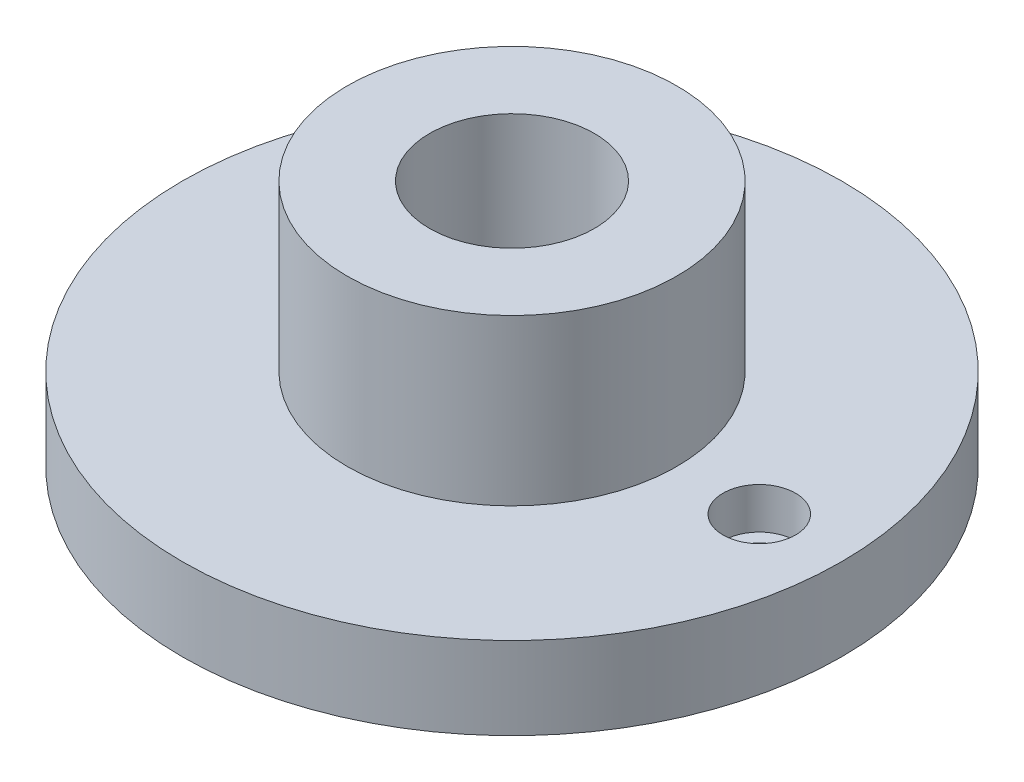
SolidWorks part; units mm, degrees
ref_plane "Front Plane" through (0, 0, 0) normal (0, 0, 1) x (1, 0, 0)
ref_plane "Top Plane" through (0, 0, 0) normal (0, 1, 0) x (1, 0, 0)
ref_plane "Right Plane" through (0, 0, 0) normal (1, 0, 0) x (0, 0, -1)
sketch "Sketch2" plane through (0, 0, 0) normal (0, 1, 0) x (1, 0, 0)
  circle A0 centre (0, 0) radius 50.8
  dimension "D1" = 101.6
extrude "Flange" add sketch "Sketch2" along normal blind 12.7
sketch "Sketch3" plane through (0, 12.7, 0) normal (0, 1, 0) x (1, 0, 0)
  circle A0 centre (0, 0) radius 25.4
extrude "Hub" add sketch "Sketch3" along normal blind 25.4
sketch "Sketch4" plane through (0, 38.1, 0) normal (0, 1, 0) x (1, 0, 0)
  circle A0 centre (0, 0) radius 12.7
  dimension "D1" = 25.4
extrude "Bore" cut sketch "Sketch4" against normal through all
hole_wizard "CBORE for 1/4 Socket Head Cap Screw2" positions "Sketch7" profile "Sketch8" counterbore size "1/4" standard "ANSI Inch" end condition up to next
sketch "Sketch7" plane through (0, 12.7, 0) normal (0, 1, 0) x (1, 0, 0)
  circle A0 centre (0, 0) radius 12.7 construction
  point P0 (38.1, 0)
  point P5 (0, 0)
  dimension "D1" = 38.1
sketch "Sketch8" plane through (38.1, 12.7, 0) normal (1, 0, 0) x (0, 0, 1)
  line L0 (0, 0) -> (0, 12.7)
  line L1 (0, 12.7) -> (3.556, 12.7)
  line L3 (3.556, 12.7) -> (3.556, 6.35)
  line L4 (3.556, 6.35) -> (5.588, 6.35)
  line L5 (5.588, 6.35) -> (5.588, 0)
  line L7 (5.588, 0) -> (0, 0)
  line L11 (0, -6.35) -> (0, 107.95) construction
  dimension "Thru Hole Dia." = 7.112
  dimension "Thru Hole Depth" = 12.7
  dimension "C'Bore Dia." = 11.176
  dimension "C'Bore Depth" = 6.35
